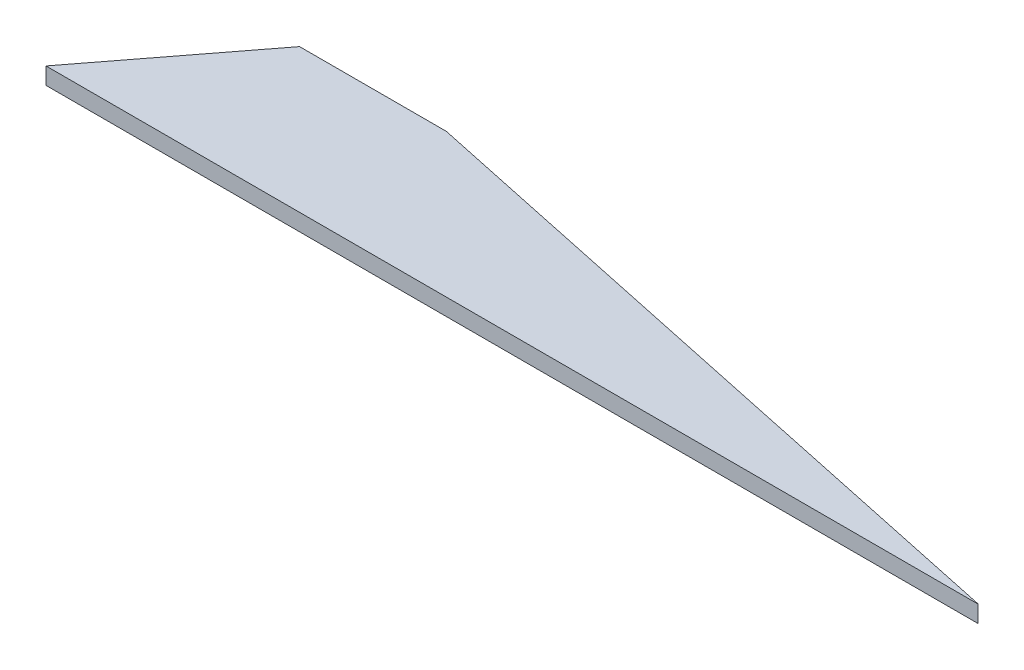
SolidWorks part; units mm, degrees
ref_plane "Front Plane" through (0, 0, 0) normal (0, 0, 1) x (1, 0, 0)
ref_plane "Top Plane" through (0, 0, 0) normal (0, 1, 0) x (1, 0, 0)
ref_plane "Right Plane" through (0, 0, 0) normal (1, 0, 0) x (0, 0, -1)
sketch "Sketch1" plane through (0, 0, 0) normal (0, 1, 0) x (1, 0, 0)
  line L1 (0, 0) -> (263.3435, 0)
  line L2 (0, 0) -> (0, 204.1914)
  line L3 (0, 204.1914) -> (263.3435, 204.1914)
  line L4 (263.3435, 0) -> (263.3435, 204.1914)
  line L5 (0, 0) -> (263.3435, 204.1914) construction
  line L6 (0, 204.1914) -> (263.3435, 0) construction
  point P4 (131.6717, 102.0957)
  dimension "D1" = 263.3435
  dimension "D2" = 204.1914
extrude "Boss-Extrude1" add sketch "Sketch1" along normal blind 4.6
sketch "Sketch3" plane through (0, 0, 0) normal (0, -1, 0) x (1, 0, 0)
  line L21 (263.3435, -0.0499) -> (78.8436, -36.6839)
  line L26 (263.3435, 0) -> (9.3435, 0)
  line L27 (41.8199, -37.055) -> (9.3435, 0.0128)
  line L28 (79.3435, -39.1211) -> (79.3435, -73.2203)
  line L29 (39.3435, -73.2203) -> (79.3435, -73.2203)
  line L30 (39.3435, -39.1211) -> (39.3435, -73.2203)
  line L31 (39.3435, -39.1211) -> (79.3435, -39.1211)
  line L32 (9.3435, 0.0128) -> (39.3435, -39.1211)
  line L33 (79.3435, -39.1211) -> (263.3435, -0.0499)
extrude "Cut-Extrude2" cut sketch "Sketch3" against normal through all flip side to cut
equation "\"MDF\"= 4.8mm"
equation "\"Foamcore\"= 4.6mm"
equation "\"GMaterial\"= \"MDF\""
equation "\"PCB\" = 1.6mm"
equation "\"BaseWidth\" = 10in"
equation "\"SkidLength\" = 1in"
equation "\"SkidClearance\" = 0.4in"
equation "\"MotorMountLength\" = 2in"
equation "\"MotorMountWidth\" = \"GMaterial\""
equation "\"MotorMountHeight\" = 2.25in"
equation "\"UnoStackWidth\" = 77.4mm"
equation "\"UnoStackLength\" = 79.8mm"
equation "\"UnoStackHeight\" = 34.2mm"
equation "\"TallHexRiserHeight\" = 22.2mm"
equation "\"PingPongBallSize\" = 40mm"
equation "\"BarrelLength\" = 9in"
equation "\"BarrelSize\" = \"PingPongBallSize\""
equation "\"PlatformLength\" = 4in"
equation "\"PlatformWidth\" = 6in"
equation "\"WheelDiameter\"=2.99213"
equation "\"ServoMountHeight\"=2.49223"
equation "\"ServoGearHeight\" = 0.95330261in"
equation "\"ServoMountLength\"= 1.53774"
equation "\"PivotHoleRadius\"= 0.616358"
equation "\"PlatformMountHeight\" = 3.19"
equation "\"TensionOffSet\"= .3mm"
equation "\"MotorMountWedge\"=0.333333"
equation "\"LaserCutterOffset\"= .3mm"
equation "\"BumperWidth\"=11"
equation "\"PitcherWheelCompression\" = 2.5mm"
equation "\"BarrelToHopperDistance\" = 0.5405in"
equation "\"PitchingWheelWidth\" = 26.2mm"
equation "\"PitchingWheelDiameter\" = 65.5mm"
equation "\"PitchingWheelMountOffset\" = 8.4mm"
equation "\"PitchingWheelInnerDiameter\" = 45.5mm"
equation "\"PitchingWheelBoltShoulder\" = 4.5mm"
equation "\"BrassCouplingLength\" = 18mm"
equation "\"PitchingMotorHeight\" = 57.0mm"
equation "\"PitchingMotorShaftTopHeight\" = \"PitchingMotorHeight\" - 44.1mm"
equation "\"PitchingMotorBodyHeight\" = 38mm"
equation "\"PitchingMotorTopShoulderHeight\" = 40.6mm - \"PitchingMotorBodyHeight\" "
equation "\"PitchingMotorBottomShoulderHeight\" = 40.2mm - \"PitchingMotorBodyHeight\""
equation "\"PitchingMotorBottomShaftHeight\" = \"PitchingMotorHeight\" - \"PitchingMotorShaftTopHeight\" - \"PitchingMotorTopShoulderHeight\" - \"PitchingMotorBodyHeight\" - \"PitchingMotorBottomShoulderHeight\""
equation "\"PitchingMotorShaftDiameter\" = 2.2mm"
equation "\"PitchingMotorBodyDiameter\" = 27.4mm"
equation "\"PitchingMotorTopShoulderDiameter\" = 9.8mm"
equation "\"PitchingMotorBottomShoulderDiameter\" = 9.8mm"
equation "\"BrassCouplingHexSize\" = 12mm"
equation "\"BrassCouplingBoreSize\" = 3.17mm"
equation "\"PitchingMotorMountingHoleDistance\" = 16mm"
equation "\"Acrylic\" = 4.4mm"
equation "\"PitchingMotorDistance\" = \"PitchingWheelDiameter\" + \"PingPongBallSize\" - \"PitcherWheelCompression\"*2"
equation "\"PitchingMotorPlatformOffset\"=1"
equation "\"ServoPlatformOffset\"=1.64173"
equation "\"BallBearingDiameter\" = 22mm"
equation "\"BallBearingWidth\" = 9mm"
equation "\"BallBearingHexShoulder\" = 9mm - 5.9mm"
equation "\"BallBearingHexSize\" = .36in"
equation "\"PlatformMountFootLength\"=0.857143"
equation "\"WheelWidth\"= 26mm"
equation "\"ServoMountReductionBackHeight\"=2.25"
equation "\"PlatformBottomWidthThird\" =  0.857143in"
equation "\"PlatformMountBackReductionHeight\"= 2.5in"
equation "\"PlatformMountBackReductionWidth\"= 3/7in"
equation "\"PlatformMountFrontReductionWidth\" =  1.46226in"
equation "\"PlatformMountFrontReductionHeight\" = 2.5in"
equation "\"HopperLongWallLength\" = 8.646in"
equation "\"HopperShortWallLength\" = 0.9571in"
equation "\"HopperHeight\" = 3.50in - \"Foamcore\""
equation "\"HoperLongSlantLength\" = 7.064in"
equation "\"HopperBottomTemplateWidth\" = 8.03903165in"
equation "\"HopperBottomTemplateLength\" = 10.367854in"
equation "\"D1@Sketch1\"=\"HopperBottomTemplateLength\""
equation "\"D2@Sketch1\"=\"HopperBottomTemplateWidth\""
equation "\"D1@Boss-Extrude1\"=\"Foamcore\""
